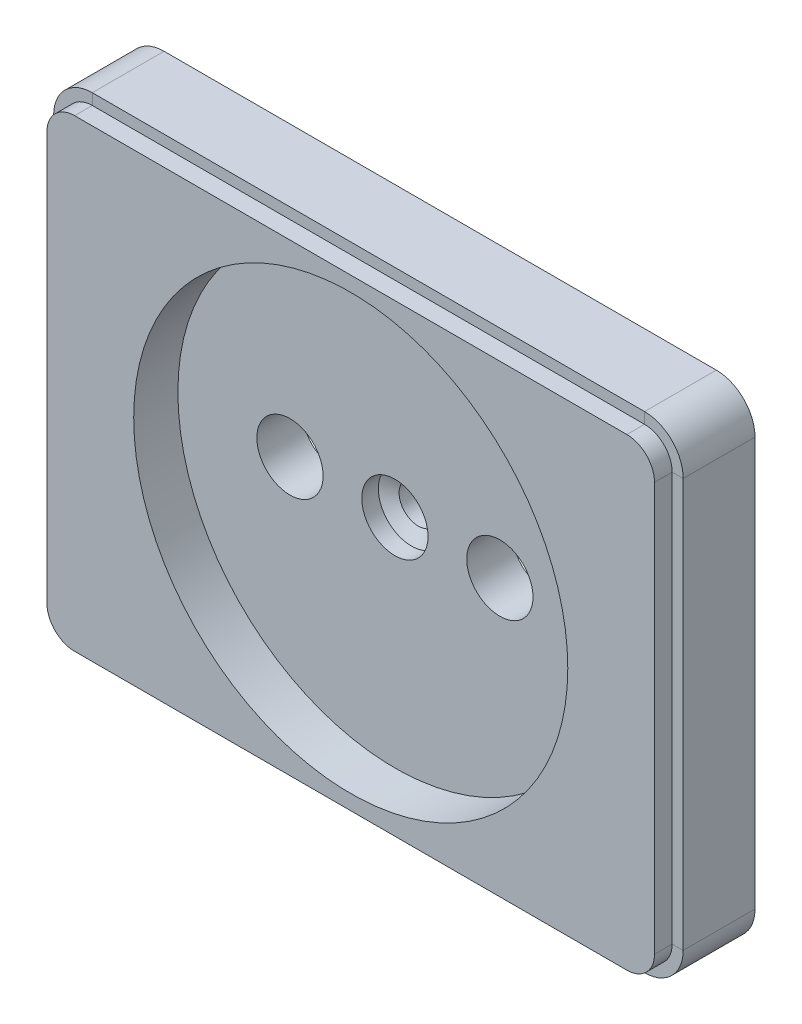
SolidWorks part; units mm, degrees
ref_plane "Front Plane" through (0, 0, 0) normal (0, 0, 1) x (1, 0, 0)
ref_plane "Top Plane" through (0, 0, 0) normal (0, 1, 0) x (1, 0, 0)
ref_plane "Right Plane" through (0, 0, 0) normal (1, 0, 0) x (0, 0, -1)
sketch "Sketch1" plane through (0, 0, 0) normal (0, 0, 1) x (1, 0, 0)
  line L0 (-9.5, 0) -> (9.5, 0)
  line L1 (-28.5, 22) -> (28.5, 22)
  line L2 (-28.5, 22) -> (-28.5, -22)
  line L3 (-28.5, -22) -> (28.5, -22)
  line L4 (28.5, 22) -> (28.5, -22)
  line L5 (-28.5, 22) -> (28.5, -22) construction
  line L6 (-28.5, -22) -> (28.5, 22) construction
  circle A0 centre (0, 0) radius 1.75
  circle A1 centre (-9.5, 0) radius 3
  circle A2 centre (9.5, 0) radius 3
  point P0 (0, 0)
  point P10 (19.1534, 0)
  point P12 (0, 0)
  point P13 (0, 0)
  point P16 (0, 0)
  dimension "D3" = 6
  dimension "D5" = 3.5
  dimension "D1" = 57
  dimension "D2" = 44
  dimension "D4" = 19
extrude "Boss-Extrude1" add sketch "Sketch1" along normal blind 8.1
sketch "Sketch2" plane through (0, 0, 8.1) normal (0, 0, 1) x (1, 0, 0)
  circle A0 centre (0, 0) radius 19.65
  dimension "D1" = 39.3
extrude "Cut-Extrude1" cut sketch "Sketch2" against normal blind 4
sketch "Sketch3" plane through (0, 0, 4.1) normal (0, 0, 1) x (1, 0, 0)
  circle A0 centre (0, 0) radius 3
  dimension "D1" = 6
extrude "Cut-Extrude2" cut sketch "Sketch3" against normal blind 1.5
sketch "Sketch4" plane through (0, 0, 0) normal (0, 1, 0) x (1, 0, 0)
  line L1 (-3, -2.6) -> (3, -2.6) construction
  line L2 (0, -2.6) -> (0, -1.1)
  line L3 (0, -1.1) -> (3, -2.6)
  line L4 (0, -2.6) -> (3, -2.6)
  line L6 (-3, -2.6) -> (3, -2.6) construction
  point P0 (2.9222, -2.9)
  dimension "D1" = 1.5
revolve "Cut-Revolve1" cut sketch "Sketch4" angle 360 about L2
fillet "Fillet2" radius 3.5 4 edges at (-28.5, 22, 4.05) (28.5, 22, 4.05) (28.5, -22, 4.05) (-28.5, -22, 4.05)
sketch "Sketch8" plane through (0, 0, 8.1) normal (0, 0, 1) x (1, 0, 0)
  line L6 (25, 22) -> (-25, 22)
  line L7 (-28.5, 18.5) -> (-28.5, -18.5)
  line L8 (-25, -22) -> (25, -22)
  line L9 (28.5, -18.5) -> (28.5, 18.5)
  line L10 (25, 22) -> (-25, 22)
  line L11 (-28.5, 18.5) -> (-28.5, -18.5)
  line L12 (-25, -22) -> (25, -22)
  line L13 (28.5, -18.5) -> (28.5, 18.5)
  arc A5 (-25, 22) -> (-28.5, 18.5) centre (-25, 18.5) ccw
  arc A6 (-25, 22) -> (-28.5, 18.5) centre (-25, 18.5) ccw
  arc A7 (-28.5, -18.5) -> (-25, -22) centre (-25, -18.5) ccw
  arc A8 (-28.5, -18.5) -> (-25, -22) centre (-25, -18.5) ccw
  arc A13 (25, -22) -> (28.5, -18.5) centre (25, -18.5) ccw
  arc A14 (25, -22) -> (28.5, -18.5) centre (25, -18.5) ccw
  arc A15 (28.5, 18.5) -> (25, 22) centre (25, 18.5) ccw
  arc A16 (28.5, 18.5) -> (25, 22) centre (25, 18.5) ccw
  dimension "D1" = 0
sketch "Sketch10" plane through (0, 0, 0) normal (0, 1, 0) x (1, 0, 0)
  line L0 (-28.5, -8.1) -> (-27.5, -8.1)
  line L1 (-27.5, -8.1) -> (-27.5, -6.5)
  line L2 (-27.5, -6.5) -> (-28.5, -6.5)
  line L3 (-28.5, -8.1) -> (-28.5, 0) construction
  line L4 (-28.5, -6.5) -> (-28.5, -8.1)
  line L5 (25, -8.1) -> (-25, -8.1) construction
  dimension "D1" = 1.6
  dimension "D2" = 1
sweep "Cut-Sweep1" cut profiles "Sketch10" path "Sketch8"
